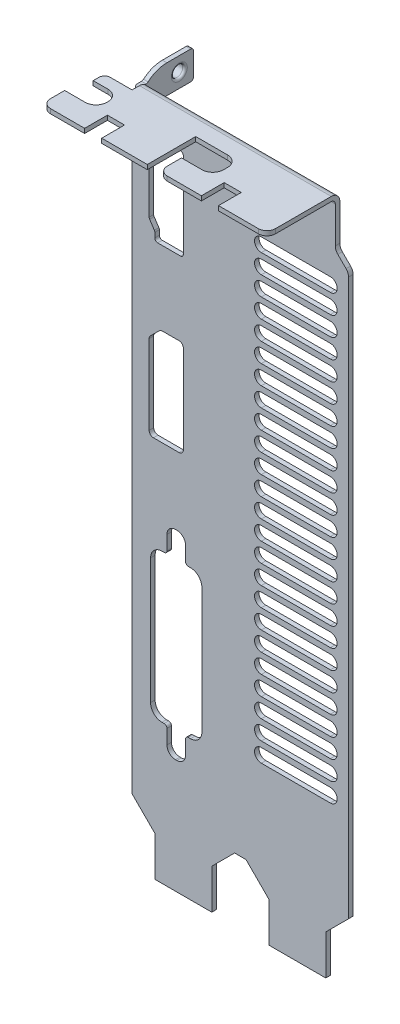
SolidWorks part; units mm, degrees
ref_plane "Front Plane" through (0, 0, 0) normal (0, 0, 1) x (1, 0, 0)
ref_plane "Top Plane" through (0, 0, 0) normal (0, 1, 0) x (1, 0, 0)
ref_plane "Right Plane" through (0, 0, 0) normal (1, 0, 0) x (0, 0, -1)
sketch "Sketch1" plane through (0, 0, 0) normal (0, 0, 1) x (1, 0, 0)
  line L0 (-19, 101.3787) -> (-19, 0)
  line L1 (-19, 0) -> (-15, -4)
  line L2 (-15, -4) -> (-15, -11)
  line L3 (-15, -11) -> (-5, -11)
  line L4 (-5, -11) -> (-5, -4)
  line L5 (-5, -4) -> (-1, 0)
  line L6 (-1, 0) -> (1, 0)
  line L7 (1, 0) -> (5, -4)
  line L8 (5, -4) -> (5, -11)
  line L9 (5, -11) -> (15, -11)
  line L10 (15, -11) -> (15, -4)
  line L11 (15, -4) -> (19, 0)
  line L12 (19, 0) -> (19, 97.5524)
  line L13 (16.6737, 109) -> (-17, 109)
  line L14 (16.6737, 109) -> (16.6737, 101.1213)
  line L15 (17.113, 100.0607) -> (18.5607, 98.613)
  line L16 (-17, 109) -> (-17, 104.6213)
  line L17 (-17.4393, 103.5607) -> (-18.5607, 102.4393)
  arc A0 (19, 97.5524) -> (18.5607, 98.613) centre (17.5, 97.5524) ccw
  arc A1 (17.113, 100.0607) -> (16.6737, 101.1213) centre (18.1737, 101.1213) cw
  arc A2 (-17, 104.6213) -> (-17.4393, 103.5607) centre (-18.5, 104.6213) cw
  arc A3 (-18.5607, 102.4393) -> (-19, 101.3787) centre (-17.5, 101.3787) ccw
  point P2 (0, 0)
  dimension "D16" = 1.5
  dimension "D19" = 1.5
  dimension "D1" = 10
  dimension "D2" = 10
  dimension "D3" = 10
  dimension "D4" = 7
  dimension "D5" = 7
  dimension "D6" = 7
  dimension "D7" = 7
  dimension "D8" = 135
  dimension "D9" = 135
  dimension "D10" = 4
  dimension "D12" = 120
  dimension "D13" = 135
  dimension "D14" = 2.3263
  dimension "D15" = 135
extrude "Boss-Extrude1" add sketch "Sketch1" along normal blind 0.7937
sketch "Sketch8" plane through (0, 0, 0.7937) normal (0, 0, 1) x (1, 0, 0)
  line L0 (-15.75, 37.5) -> (-15.75, 15.5)
  line L1 (-13.75, 13.5) -> (-13.375, 13.5)
  line L2 (-12.875, 13) -> (-12.875, 10.5)
  line L3 (-11.375, 9) -> (-11.125, 9)
  line L4 (-9.625, 10.5) -> (-9.625, 13)
  line L5 (-9.125, 13.5) -> (-8.75, 13.5)
  line L6 (-6.75, 15.5) -> (-6.75, 37.5)
  line L7 (-6.75, 26.5) -> (-15.75, 26.5) construction
  line L8 (-15, -11) -> (-5, -11) construction
  line L9 (-19, 101.3787) -> (-19, 0) construction
  line L10 (-11.25, 9) -> (-11.25, 10.9703) construction
  line L11 (-11.25, 29.9753) -> (-11.25, 23.0247) construction
  line L12 (-11.25, 44) -> (-11.25, 42.0297) construction
  line L13 (-9.125, 39.5) -> (-8.75, 39.5)
  line L14 (-9.625, 42.5) -> (-9.625, 40)
  line L15 (-11.375, 44) -> (-11.125, 44)
  line L16 (-12.875, 40) -> (-12.875, 42.5)
  line L17 (-13.75, 39.5) -> (-13.375, 39.5)
  line L18 (-14.2197, 72.7803) -> (-15.7803, 71.2197)
  line L19 (-10.75, 73) -> (-13.6893, 73)
  line L20 (-10, 72.25) -> (-10, 56.75)
  line L21 (-10.75, 56) -> (-15.25, 56)
  line L22 (-16, 70.6893) -> (-16, 56.75)
  line L23 (-15.916, 88.874) -> (-15.084, 87.626)
  line L24 (-10.5, 102) -> (-14.5, 102)
  line L25 (-10, 101.5) -> (-10, 86.5)
  line L26 (-10.5, 86) -> (-14.5, 86)
  line L27 (-16, 98.8486) -> (-16, 89.1514)
  line L28 (-15, 87.3486) -> (-15, 86.5)
  line L29 (-10, 94) -> (-12.0883, 94) construction
  line L30 (-15, 100.6514) -> (-15, 101.5)
  line L31 (-15.916, 99.126) -> (-15.084, 100.374)
  arc A0 (-15.75, 15.5) -> (-13.75, 13.5) centre (-13.75, 15.5) ccw
  arc A1 (-8.75, 13.5) -> (-6.75, 15.5) centre (-8.75, 15.5) ccw
  arc A2 (-12.875, 13) -> (-13.375, 13.5) centre (-13.375, 13) ccw
  arc A3 (-9.625, 13) -> (-9.125, 13.5) centre (-9.125, 13) cw
  arc A4 (-11.375, 9) -> (-12.875, 10.5) centre (-11.375, 10.5) cw
  arc A5 (-11.125, 9) -> (-9.625, 10.5) centre (-11.125, 10.5) ccw
  arc A6 (-11.125, 44) -> (-9.625, 42.5) centre (-11.125, 42.5) cw
  arc A7 (-11.375, 44) -> (-12.875, 42.5) centre (-11.375, 42.5) ccw
  arc A8 (-9.625, 40) -> (-9.125, 39.5) centre (-9.125, 40) ccw
  arc A9 (-12.875, 40) -> (-13.375, 39.5) centre (-13.375, 40) cw
  arc A10 (-8.75, 39.5) -> (-6.75, 37.5) centre (-8.75, 37.5) cw
  arc A11 (-15.75, 37.5) -> (-13.75, 39.5) centre (-13.75, 37.5) cw
  arc A12 (-13.6893, 73) -> (-14.2197, 72.7803) centre (-13.6893, 72.25) ccw
  arc A13 (-15.7803, 71.2197) -> (-16, 70.6893) centre (-15.25, 70.6893) ccw
  arc A14 (-16, 56.75) -> (-15.25, 56) centre (-15.25, 56.75) ccw
  arc A15 (-10.75, 56) -> (-10, 56.75) centre (-10.75, 56.75) ccw
  arc A16 (-10, 72.25) -> (-10.75, 73) centre (-10.75, 72.25) ccw
  arc A17 (-10.5, 102) -> (-10, 101.5) centre (-10.5, 101.5) cw
  arc A18 (-10, 86.5) -> (-10.5, 86) centre (-10.5, 86.5) cw
  arc A19 (-14.5, 86) -> (-15, 86.5) centre (-14.5, 86.5) cw
  arc A20 (-15, 87.3486) -> (-15.084, 87.626) centre (-15.5, 87.3486) ccw
  arc A21 (-15.916, 88.874) -> (-16, 89.1514) centre (-15.5, 89.1514) cw
  arc A22 (-16, 98.8486) -> (-15.916, 99.126) centre (-15.5, 98.8486) cw
  arc A23 (-15, 100.6514) -> (-15.084, 100.374) centre (-15.5, 100.6514) cw
  arc A24 (-15, 101.5) -> (-14.5, 102) centre (-14.5, 101.5) cw
  point P30 (-11.25, 26.5)
  point P56 (-14, 73)
  point P59 (-16, 71)
  dimension "D7" = 2
  dimension "D8" = 0.5
  dimension "D9" = 1.5
  dimension "D16" = 0.75
  dimension "D18" = 0.5
  dimension "D1" = 17.5
  dimension "D2" = 4.5
  dimension "D3" = 20
  dimension "D4" = 3.25
  dimension "D5" = 9
  dimension "D6" = 3.25
  dimension "D10" = 67
  dimension "D11" = 17
  dimension "D12" = 3
  dimension "D13" = 6
  dimension "D14" = 2
  dimension "D15" = 135
  dimension "D17" = 97
  dimension "D20" = 1
extrude "Cut-Extrude2" cut sketch "Sketch8" against normal up to next
sketch "Sketch9" plane through (0, 0, 0.7937) normal (0, 0, 1) x (1, 0, 0)
  line L0 (3.6906, 16) -> (15.8094, 16)
  line L1 (3.6906, 18.3813) -> (15.8094, 18.3813)
  line L2 (5, -11) -> (15, -11) construction
  line L3 (17, 17.1906) -> (17, 14.1369) construction
  line L4 (19, 0) -> (19, 97.5524) construction
  line L5 (2.5, 17.1906) -> (2.5, 12.0653) construction
  arc A0 (15.8094, 16) -> (15.8094, 18.3813) centre (15.8094, 17.1906) ccw
  arc A1 (3.6906, 16) -> (3.6906, 18.3813) centre (3.6906, 17.1906) cw
  dimension "D1" = 27
  dimension "D2" = 2.3813
  dimension "D3" = 2
  dimension "D4" = 14.5
extrude "Cut-Extrude3" cut sketch "Sketch9" against normal up to next
pattern_linear "LPattern1" count 24 spacing 3.375 along (0, 1, 0) of "Cut-Extrude3"
sketch "Sketch10" plane through (0, 109, 0) normal (0, 1, 0) x (1, 0, 0)
  line L0 (16.6737, -0.7937) -> (16.6737, -11.2937)
  line L1 (15.1737, -12.7937) -> (8.1737, -12.7938)
  line L2 (8.1737, -12.7938) -> (8.1737, -8.7938)
  line L3 (8.1737, -8.7938) -> (5.1737, -8.7938)
  line L4 (5.1737, -8.7938) -> (5.1737, -12.7937)
  line L5 (5.1737, -12.7937) -> (-0.8263, -12.7938)
  line L6 (-2.3263, -11.2937) -> (-2.3263, -8.7938)
  line L7 (-2.3263, -8.7938) -> (1.2737, -8.7938)
  line L8 (3.1737, -6.8937) -> (3.1737, -6.1938)
  line L9 (1.2737, -4.2938) -> (-4.3263, -4.2938)
  line L10 (-4.3263, -4.2938) -> (-4.3263, -12.7938)
  line L11 (-4.3263, -12.7938) -> (-12.3263, -12.7938)
  line L12 (-12.3263, -12.7938) -> (-12.3263, -8.7938)
  line L13 (-12.3263, -8.7938) -> (-15.3263, -8.7938)
  line L14 (-15.3263, -8.7938) -> (-15.3263, -12.7938)
  line L15 (-15.3263, -12.7938) -> (-21.3263, -12.7938)
  line L16 (-22.8263, -11.2937) -> (-22.8263, -8.7938)
  line L17 (-22.8263, -8.7938) -> (-19.2263, -8.7938)
  line L18 (-17.3263, -6.8937) -> (-17.3263, -6.6938)
  line L19 (-19.2263, -4.7938) -> (-21.8263, -4.7938)
  line L20 (-21.8263, -4.7938) -> (-21.8263, -3.7938)
  line L21 (-20.8263, -2.7938) -> (-17, -2.7938)
  line L22 (-17, -2.7938) -> (-17, -0.7937)
  line L23 (16.6737, -0.7937) -> (-17, -0.7937) construction
  line L24 (-17, -0.7937) -> (16.6737, -0.7937)
  arc A0 (-22.8263, -11.2937) -> (-21.3263, -12.7938) centre (-21.3263, -11.2938) ccw
  arc A1 (-2.3263, -11.2937) -> (-0.8263, -12.7938) centre (-0.8263, -11.2938) ccw
  arc A2 (15.1737, -12.7937) -> (16.6737, -11.2937) centre (15.1737, -11.2937) ccw
  arc A3 (1.2737, -4.2938) -> (3.1737, -6.1938) centre (1.2737, -6.1938) cw
  arc A4 (3.1737, -6.8937) -> (1.2737, -8.7938) centre (1.2737, -6.8938) cw
  arc A5 (-17.3263, -6.6938) -> (-19.2263, -4.7938) centre (-19.2263, -6.6938) ccw
  arc A6 (-17.3263, -6.8937) -> (-19.2263, -8.7938) centre (-19.2263, -6.8938) cw
  arc A7 (-20.8263, -2.7938) -> (-21.8263, -3.7938) centre (-20.8263, -3.7938) ccw
  dimension "D17" = 1.5
  dimension "D2" = 1.9
  dimension "D5" = 1
  dimension "D3" = 3
  dimension "D4" = 4
  dimension "D6" = 2
  dimension "D7" = 8
  dimension "D8" = 3
  dimension "D10" = 4.5
  dimension "D11" = 4
  dimension "D12" = 7.5
  dimension "D13" = 5.5
  dimension "D14" = 4
  dimension "D16" = 2
extrude "Boss-Extrude5" add sketch "Sketch10" against normal blind 0.7937
fillet "Fillet4" radius 1.5 1 edges at (-0.1632, 109, 0)
fillet "Fillet5" radius 0.725 1 edges at (-0.1632, 108.2062, 0.7937)
sketch "Sketch11" plane through (-17, 0, 0) normal (-1, 0, 0) x (0, 0, 1)
  line L0 (0, 107.5) -> (0, 104.6213) construction
  line L1 (0.7937, 103.8653) -> (0, 103.8653)
  line L2 (0.7937, 103.8653) -> (0.7937, 107.4812)
  line L3 (0.7937, 107.4812) -> (0, 107.4812)
  line L4 (0, 103.8653) -> (0, 107.4812)
  line L5 (0.7937, 107.4812) -> (0.7937, 104.6213) construction
extrude "Boss-Extrude6" add sketch "Sketch11" along normal up to surface (2 mm away) up to face at (-19, 50.6893, 0.3969)
sketch "Sketch12" plane through (-19, 0, 0) normal (-1, 0, 0) x (0, 0, 1)
  line L0 (0, 103.8653) -> (0, 103.5607) construction
  line L1 (0, 103.8653) -> (0, 107.4813) construction
  line L2 (0, 103.8653) -> (-8.7063, 103.8653)
  line L3 (-9.2063, 104.3653) -> (-9.2063, 108.3653)
  line L4 (-8.7063, 108.8653) -> (-4.5213, 108.8653)
  line L5 (-0.9858, 107.4009) -> (-1.2126, 107.6277)
  line L6 (-0.8591, 107.4813) -> (0, 107.4813)
  line L7 (0, 107.4813) -> (0.7937, 107.4813) construction
  line L8 (0.7937, 107.4813) -> (0.7937, 103.8653) construction
  line L9 (-9.2063, 106.3653) -> (-10.2599, 106.3653) construction
  line L10 (-7.7063, 106.3653) -> (-7.7063, 109.3729) construction
  circle A0 centre (-6.7063, 106.3653) radius 1
  arc A3 (-1.2126, 107.6277) -> (-0.8591, 107.4813) centre (-0.8591, 107.9813) ccw
  arc A4 (-8.7063, 108.8653) -> (-9.2063, 108.3653) centre (-8.7063, 108.3653) ccw
  arc A5 (-9.2063, 104.3653) -> (-8.7063, 103.8653) centre (-8.7063, 104.3653) ccw
  arc A6 (-4.5213, 108.8653) -> (-0.9858, 107.4009) centre (-4.5213, 103.8653) cw
  dimension "D5" = 2
  dimension "D7" = 5
  dimension "D2" = 10
  dimension "D3" = 5
  dimension "D6" = 1.5
extrude "Boss-Extrude7" add sketch "Sketch12" against normal blind 0.7937
fillet "Fillet6" radius 1 1 edges at (-19, 105.6733, 0.7937)
fillet "Fillet7" radius 0.3 1 edges at (-18.2063, 105.6733, 0)
fillet "Fillet8" radius 0.4 1 edges at (-18.2063, 105.3653, -6.7063)
sketch "Sketch13" plane through (-19, 0, 0) normal (-1, 0, 0) x (0, 0, 1)
  circle A0 centre (-6.7063, 106.3653) radius 1
  circle A1 centre (-6.7063, 106.3653) radius 1.5
  dimension "D1" = 3
extrude "Boss-Extrude8" add sketch "Sketch13" along normal blind 1
